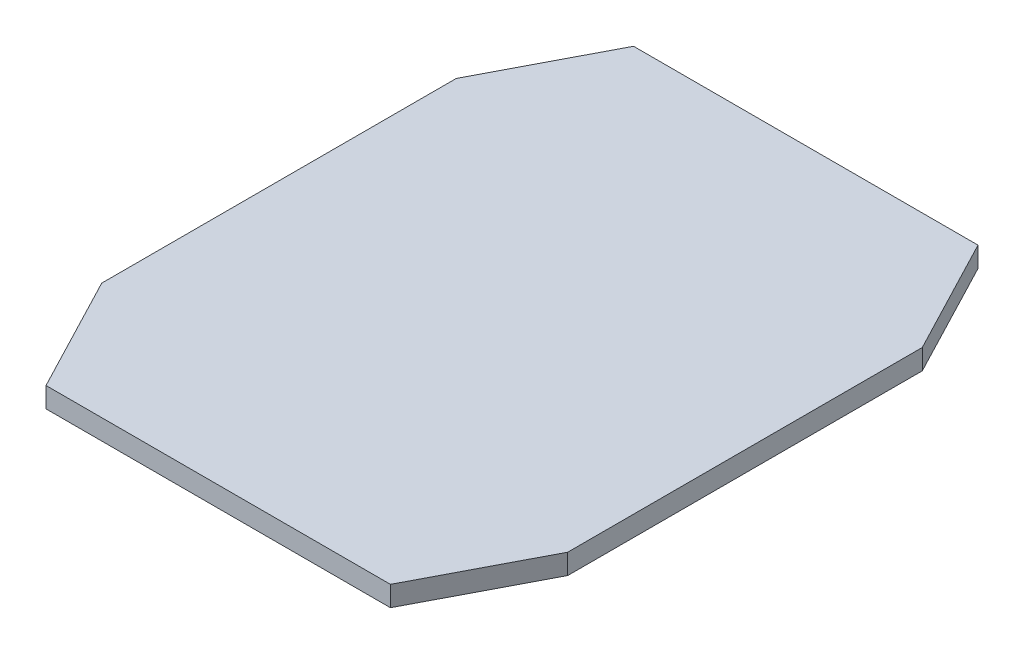
SolidWorks part; units mm, degrees
ref_plane "Front Plane" through (0, 0, 0) normal (0, 0, 1) x (1, 0, 0)
ref_plane "Top Plane" through (0, 0, 0) normal (0, 1, 0) x (1, 0, 0)
ref_plane "Right Plane" through (0, 0, 0) normal (1, 0, 0) x (0, 0, -1)
sketch "Sketch1" plane through (0, 0, 0) normal (0, 1, 0) x (1, 0, 0)
  line L1 (-155, 145) -> (155, 145)
  line L2 (-155, 145) -> (-155, -145)
  line L3 (-155, -145) -> (155, -145)
  line L4 (155, 145) -> (155, -145)
  line L5 (-155, 145) -> (155, -145) construction
  line L6 (-155, -145) -> (155, 145) construction
  point P0 (0, 0)
  dimension "D1" = 310
  dimension "D2" = 290
extrude "Boss-Extrude1" add sketch "Sketch1" along normal blind 10
sketch "Sketch2" plane through (0, 10, 0) normal (0, 1, 0) x (1, 0, 0)
  line L0 (-85, 145) -> (-115, 87.5)
  line L1 (155, 145) -> (-155, 145) construction
  line L2 (-115, 87.5) -> (-115, -87.5)
  line L5 (-115, -87.5) -> (-85, -145)
  line L6 (-155, -145) -> (155, -145) construction
  line L7 (-85, -145) -> (-155, -145)
  line L8 (-155, -145) -> (-155, 145)
  line L9 (-155, 145) -> (-85, 145)
  line L10 (0, -200.75) -> (0, 200.75) construction
  line L11 (155, -145) -> (155, 145)
  line L12 (85, -145) -> (155, -145)
  line L13 (115, -87.5) -> (85, -145)
  line L14 (115, 87.5) -> (115, -87.5)
  line L15 (85, 145) -> (115, 87.5)
  line L16 (155, 145) -> (85, 145)
  dimension "D1" = 70
  dimension "D2" = 175
  dimension "D3" = 40
extrude "Cut-Extrude1" cut sketch "Sketch2" against normal through all
